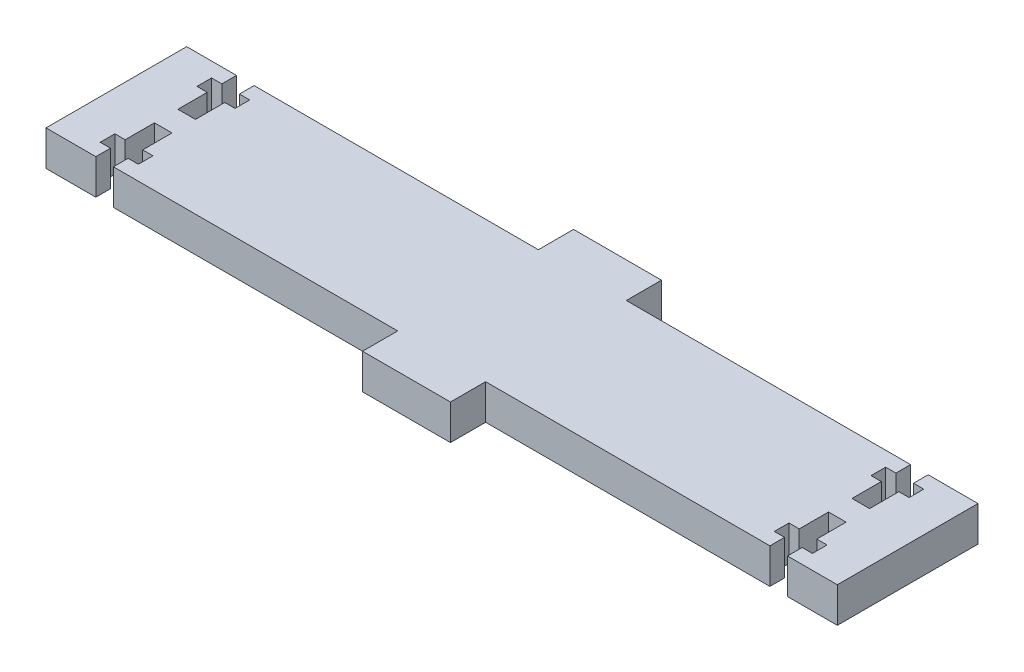
SolidWorks part; units mm, degrees
ref_plane "Front Plane" through (0, 0, 0) normal (0, 0, 1) x (1, 0, 0)
ref_plane "Top Plane" through (0, 0, 0) normal (0, 1, 0) x (1, 0, 0)
ref_plane "Right Plane" through (0, 0, 0) normal (1, 0, 0) x (0, 0, -1)
sketch "Sketch1" plane through (0, 0, 0) normal (0, 1, 0) x (1, 0, 0)
  line L0 (-1342.2955, 0) -> (65772.4784, 0) construction
  line L1 (0, -1342.2955) -> (0, 65772.4784) construction
  line L2 (-57.5, 12) -> (-57.5, -12) construction
  line L3 (-67.5, 12) -> (67.5, 12)
  line L4 (-67.5, 12) -> (-67.5, -12)
  line L5 (-67.5, -12) -> (67.5, -12)
  line L6 (67.5, 12) -> (67.5, -12)
  line L7 (-67.5, 12) -> (67.5, -12) construction
  line L8 (-67.5, -12) -> (67.5, 12) construction
  line L9 (-59, 12) -> (-56, 12)
  line L10 (-59, 12) -> (-59, 2)
  line L11 (-59, 2) -> (-56, 2)
  line L12 (-56, 12) -> (-56, 2)
  line L13 (-60.75, 9.5) -> (-54.25, 9.5)
  line L14 (-60.75, 9.5) -> (-60.75, 7)
  line L15 (-60.75, 7) -> (-54.25, 7)
  line L16 (-54.25, 9.5) -> (-54.25, 7)
  line L17 (57.5, 12) -> (57.5, -12) construction
  line L18 (54.25, 9.5) -> (54.25, 7)
  line L19 (60.75, 7) -> (54.25, 7)
  line L20 (60.75, 9.5) -> (60.75, 7)
  line L21 (60.75, 9.5) -> (54.25, 9.5)
  line L22 (56, 12) -> (56, 2)
  line L23 (59, 2) -> (56, 2)
  line L24 (59, 12) -> (59, 2)
  line L25 (59, 12) -> (56, 12)
  line L26 (59, -12) -> (56, -12)
  line L27 (59, -12) -> (59, -2)
  line L28 (59, -2) -> (56, -2)
  line L29 (56, -12) -> (56, -2)
  line L30 (60.75, -9.5) -> (54.25, -9.5)
  line L31 (60.75, -9.5) -> (60.75, -7)
  line L32 (60.75, -7) -> (54.25, -7)
  line L33 (54.25, -9.5) -> (54.25, -7)
  line L34 (-54.25, -9.5) -> (-54.25, -7)
  line L35 (-60.75, -7) -> (-54.25, -7)
  line L36 (-60.75, -9.5) -> (-60.75, -7)
  line L37 (-60.75, -9.5) -> (-54.25, -9.5)
  line L38 (-56, -12) -> (-56, -2)
  line L39 (-59, -2) -> (-56, -2)
  line L40 (-59, -12) -> (-59, -2)
  line L41 (-59, -12) -> (-56, -12)
  line L42 (-7.5, -12) -> (7.5, -18) construction
  line L43 (-7.5, 18) -> (7.5, 18)
  line L44 (-7.5, 18) -> (-7.5, 12)
  line L45 (-7.5, 12) -> (7.5, 12)
  line L46 (7.5, 18) -> (7.5, 12)
  line L47 (-7.5, 18) -> (7.5, 12) construction
  line L48 (-7.5, 12) -> (7.5, 18) construction
  line L49 (-7.5, -18) -> (7.5, -12) construction
  line L50 (7.5, -18) -> (7.5, -12)
  line L51 (-7.5, -12) -> (7.5, -12)
  line L52 (-7.5, -18) -> (-7.5, -12)
  line L53 (-7.5, -18) -> (7.5, -18)
  point P4 (0, 0)
  point P46 (0, 15)
  point P56 (0, -15)
  dimension "D1" = 135
  dimension "D2" = 24
  dimension "D3" = 10
  dimension "D4" = 3
  dimension "D5" = 6.5
  dimension "D6" = 2.5
  dimension "D7" = 5
  dimension "D9" = 57.5
  dimension "D8" = 57.5
  dimension "D10" = 15
  dimension "D11" = 6
extrude "Boss-Extrude1" add sketch "Sketch1" along normal blind 6 contours L5 L40 L37 L36 L35 L39 L38 L34 L29 L30 L33 L32 L28 L27 L31 L6 L3 L24 L21 L20 L19 L23 L22 L18 L12 L13 L16 L15 L11 L10 L14 | L46 L43 L44 L3 | L52 L53 L50 L5
equation "\"Frame_Size\" = 220"
equation "\"Frame_Thickness\" = 6"
equation "\"Arm_Width\" = 30"
equation "\"Motor_Mount_Hole_Diameter\" = 8"
equation "\"Motor_Shaft_Diameter\" = 3"
equation "\"Screw_Nut_Diameter\" = 6.5"
equation "\"Screw_Diameter\" = 3"
equation "\"Screw_Shaft_Length\" = 10"
equation "\"Screw_Hole_Separation_C2C\" = 20"
equation "\"Solder_Board_Small_Screw_Hole_Separation\" = 37"
equation "\"Solder_Board_Small_Screw_Hole_Diameter\" = 3.3"
equation "\"Solder_Board_Small_Length\" = 45.72"
equation "\"Solder_Board_Small_Width\" = 33.02"
equation "\"Solder_Board_Small_Thickness\" = 1.6"
equation "\"ESC_Length\" = 35"
equation "\"ESC_Width\" = 17"
equation "\"ESC_Thickness\" = 5"
equation "\"Battery_Length\" = 105"
equation "\"Battery_Width\" = 33"
equation "\"Battery_Thickness\" = 24"
equation "\"Battery_Holder_Screw_Hole_Distance_Long\" = 115"
equation "\"Battery_Holder_Screw_Hole_Distance_Short\" = 40"
equation "\"D1@Sketch1\"=\"Battery_Holder_Screw_Hole_Distance_Long\"+ 20"
equation "\"D2@Sketch1\"=\"Battery_Thickness\""
equation "\"D3@Sketch1\"=\"Screw_Shaft_Length\""
equation "\"D4@Sketch1\"=\"Screw_Diameter\""
equation "\"D5@Sketch1\"=\"Screw_Nut_Diameter\""
equation "\"Screw_Nut_Thickness\" = 2.5"
equation "\"D6@Sketch1\"=\"Screw_Nut_Thickness\""
equation "\"D7@Sketch1\"=\"Screw_Shaft_Length\"/2"
equation "\"D9@Sketch1\"=\"Battery_Holder_Screw_Hole_Distance_Long\"/2"
equation "\"D8@Sketch1\"=\"Battery_Holder_Screw_Hole_Distance_Long\"/2"
equation "\"D1@Boss-Extrude1\"=\"Frame_Thickness\""
equation "\"Tooth_Width\" = 15"
equation "\"D10@Sketch1\"=\"Tooth_Width\""
equation "\"D11@Sketch1\"=\"Frame_Thickness\""
